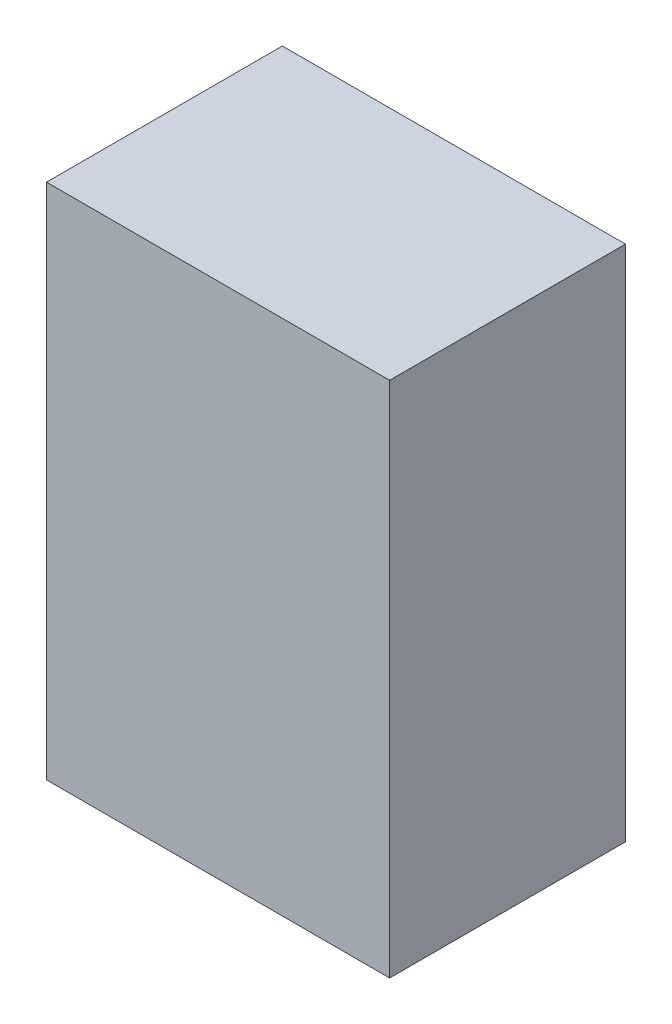
SolidWorks part; units mm, degrees
ref_plane "Front Plane" through (0, 0, 0) normal (0, 0, 1) x (1, 0, 0)
ref_plane "Top Plane" through (0, 0, 0) normal (0, 1, 0) x (1, 0, 0)
ref_plane "Right Plane" through (0, 0, 0) normal (1, 0, 0) x (0, 0, -1)
sketch "Sketch1" plane through (0, 0, 0) normal (0, 0, 1) x (1, 0, 0)
  line L1 (-29.1, -43.9) -> (29.1, -43.9)
  line L2 (-29.1, -43.9) -> (-29.1, 43.9)
  line L3 (-29.1, 43.9) -> (29.1, 43.9)
  line L4 (29.1, -43.9) -> (29.1, 43.9)
  line L5 (-29.1, -43.9) -> (29.1, 43.9) construction
  line L6 (-29.1, 43.9) -> (29.1, -43.9) construction
  point P0 (0, 0)
  dimension "D1" = 87.8
  dimension "D2" = 58.2
extrude "Boss-Extrude1" add sketch "Sketch1" along normal mid plane 40
